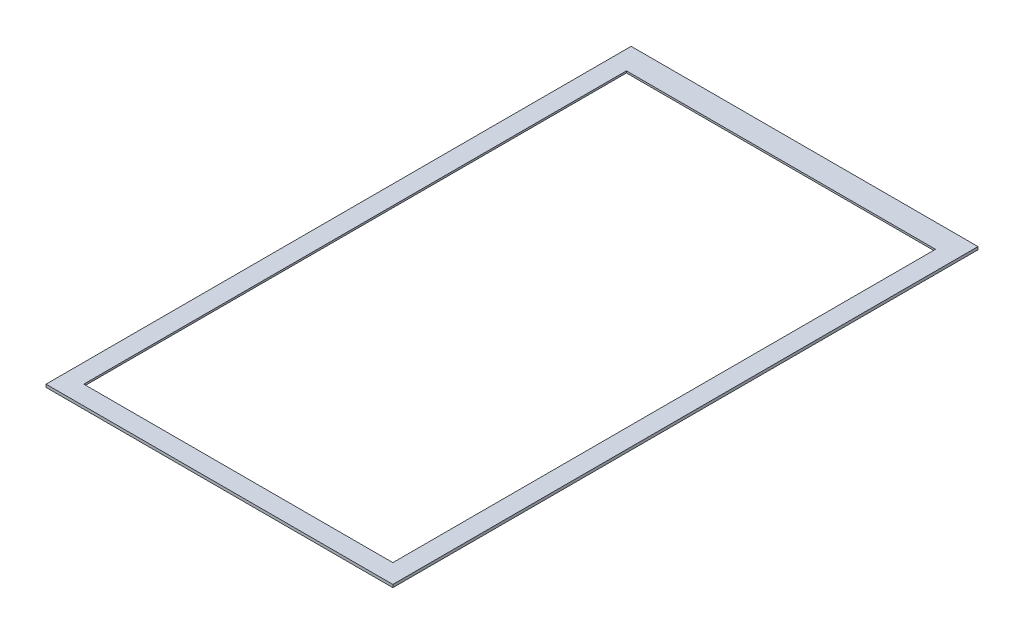
SolidWorks part; units mm, degrees
ref_plane "Front Plane" through (0, 0, 0) normal (0, 0, 1) x (1, 0, 0)
ref_plane "Top Plane" through (0, 0, 0) normal (0, 1, 0) x (1, 0, 0)
ref_plane "Right Plane" through (0, 0, 0) normal (1, 0, 0) x (0, 0, -1)
sketch "Sketch1" plane through (0, 0, 0) normal (0, 1, 0) x (1, 0, 0)
  line L1 (-367.5, 620) -> (367.5, 620)
  line L2 (-367.5, 620) -> (-367.5, -620)
  line L3 (-367.5, -620) -> (367.5, -620)
  line L4 (367.5, 620) -> (367.5, -620)
  line L5 (-367.5, 620) -> (367.5, -620) construction
  line L6 (-367.5, -620) -> (367.5, 620) construction
  line L7 (-327.5, 570) -> (327.5, 570)
  line L8 (-327.5, 570) -> (-327.5, -580)
  line L9 (-327.5, -580) -> (327.5, -580)
  line L10 (327.5, 570) -> (327.5, -580)
  line L11 (-327.5, 570) -> (327.5, -580) construction
  line L12 (-327.5, -580) -> (327.5, 570) construction
  point P0 (0, 0)
  point P6 (0, -5)
  dimension "D1" = 1240
  dimension "D2" = 735
  dimension "D3" = 40
  dimension "D4" = 40
  dimension "D5" = 40
  dimension "D6" = 50
extrude "Boss-Extrude1" add sketch "Sketch1" along normal blind 6
sketch "Sketch2" plane through (0, 0, 0) normal (0, -1, 0) x (1, 0, 0)
  line L0 (327.5, 580) -> (327.5, -570) construction
  line L1 (348.5, -591) -> (-348.5, -591)
  line L2 (348.5, -591) -> (348.5, 601)
  line L3 (348.5, 601) -> (-348.5, 601)
  line L4 (-348.5, -591) -> (-348.5, 601)
  line L5 (348.5, -591) -> (-348.5, 601) construction
  line L6 (348.5, 601) -> (-348.5, -591) construction
  line L7 (-327.5, -570) -> (-327.5, 580) construction
  line L8 (-327.5, 580) -> (327.5, 580) construction
  line L9 (327.5, -570) -> (-327.5, -570) construction
  point P0 (0, 5)
  dimension "D1" = 21
  dimension "D2" = 21
  dimension "D3" = 21
  dimension "D4" = 21
extrude "Cut-Extrude1" cut sketch "Sketch2" against normal blind 2
